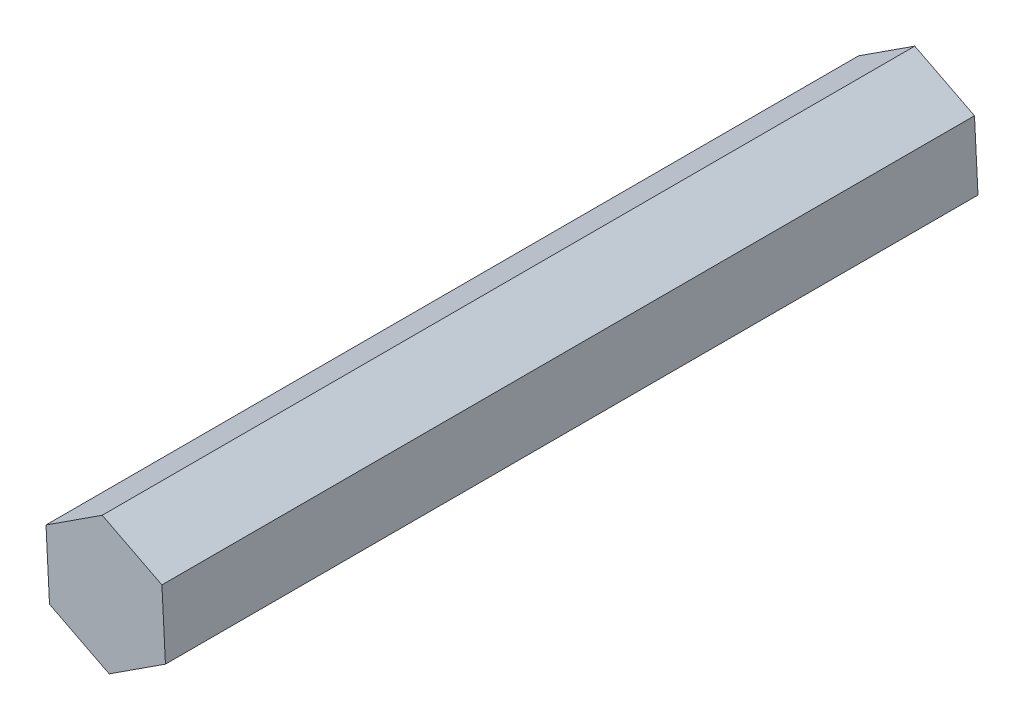
SolidWorks part; units mm, degrees
ref_plane "Front Plane" through (0, 0, 0) normal (0, 0, 1) x (1, 0, 0)
ref_plane "Top Plane" through (0, 0, 0) normal (0, 1, 0) x (1, 0, 0)
ref_plane "Right Plane" through (0, 0, 0) normal (1, 0, 0) x (0, 0, -1)
sketch "Sketch2" plane through (0, 0, 0) normal (0, 0, 1) x (1, 0, 0)
  line L1 (-6.5329, 3.3293) -> (-6.1497, -3.993)
  line L2 (-6.1497, -3.993) -> (0.3832, -7.3223)
  line L3 (0.3832, -7.3223) -> (6.5329, -3.3293)
  line L4 (6.5329, -3.3293) -> (6.1497, 3.993)
  line L5 (6.1497, 3.993) -> (-0.3832, 7.3223)
  line L6 (-0.3832, 7.3223) -> (-6.5329, 3.3293)
  circle A0 centre (0, 0) radius 6.35 construction
  point P1 (6.3413, 0.3319)
  dimension "D1" = 12.7
extrude "Boss-Extrude2" add sketch "Sketch2" along normal blind 88.9
sketch "Sketch3" plane through (0, 0, 88.9) normal (0, 0, 1) x (1, 0, 0)
  circle A0 centre (0, 0) radius 6.35
  dimension "D1" = 12.7
equation "\"4n\"=3.75"
